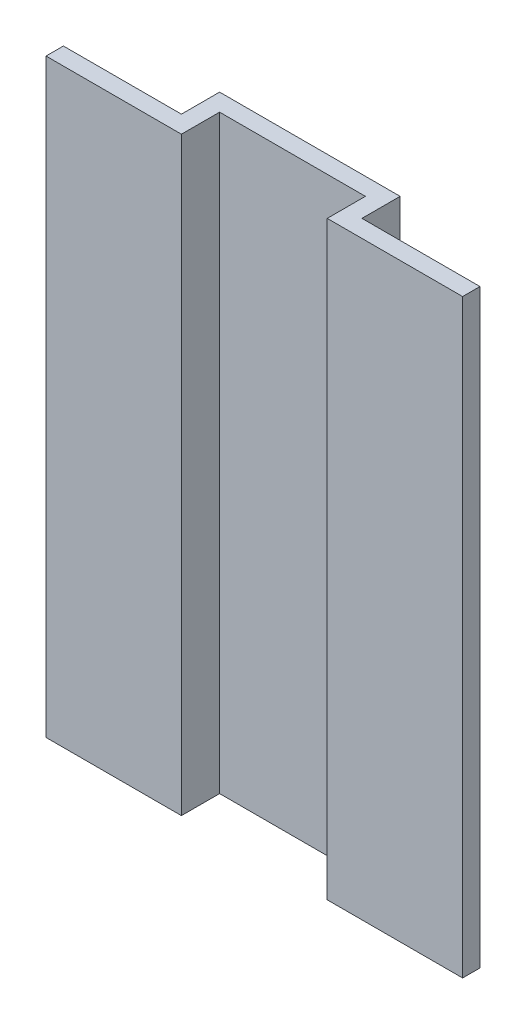
SolidWorks part; units mm, degrees
ref_plane "Front Plane" through (0, 0, 0) normal (0, 0, 1) x (1, 0, 0)
ref_plane "Top Plane" through (0, 0, 0) normal (0, 1, 0) x (1, 0, 0)
ref_plane "Right Plane" through (0, 0, 0) normal (1, 0, 0) x (0, 0, -1)
sketch "Sketch1" plane through (0, 0, 0) normal (0, 1, 0) x (1, 0, 0)
  line L0 (-60, -5) -> (-21, -5)
  line L1 (-60, 0) -> (-26, 0)
  line L2 (-60, 0) -> (-60, -5)
  line L4 (60, 0) -> (60, -5)
  line L11 (-26, 0) -> (-26, 11)
  line L12 (-26, 11) -> (26, 11)
  line L13 (26, 11) -> (26, 0)
  line L14 (26, 0) -> (60, 0)
  line L17 (-21, -5) -> (-21, 6)
  line L18 (-21, 6) -> (21, 6)
  line L19 (21, 6) -> (21, -5)
  line L20 (-21, 0) -> (-21, 6) construction
  line L21 (21, 6) -> (21, 0) construction
  line L22 (21, -5) -> (60, -5)
  point P1 (-59.0033, -5)
  point P4 (-61.0558, -5)
  point P5 (0, 11)
  point P8 (59.1271, -5)
  point P17 (-20.5, -5)
  point P19 (20.5, -5)
  dimension "D1" = 120
  dimension "D2" = 11
  dimension "D3" = 52
  dimension "D4" = 60
  dimension "D5" = 5
  dimension "D6" = 5
  dimension "D8" = 5
extrude "Boss-Extrude1" add sketch "Sketch1" along normal mid plane 170
